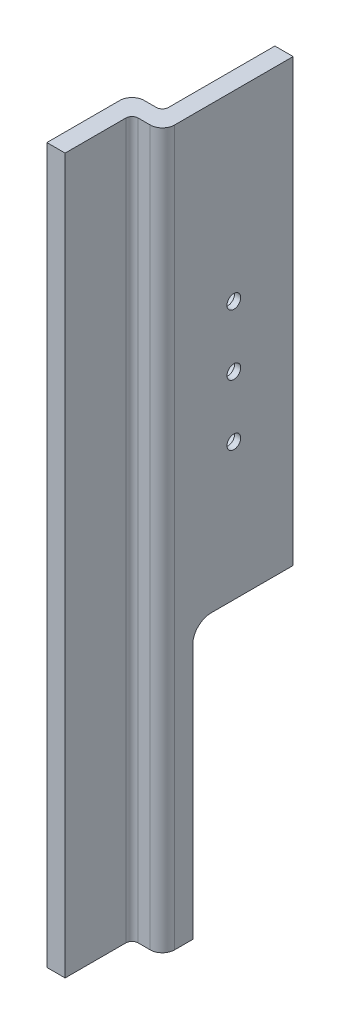
SolidWorks part; units mm, degrees
ref_plane "Piano frontale" through (0, 0, 0) normal (0, 0, 1) x (1, 0, 0)
ref_plane "Piano superiore" through (0, 0, 0) normal (0, 1, 0) x (1, 0, 0)
ref_plane "Piano destro" through (0, 0, 0) normal (1, 0, 0) x (0, 0, -1)
ref_plane "Piano1" through (6, 0, 0) normal (1, 0, 0) x (0, 0, -1)
sketch "Schizzo1" plane through (6, 0, 0) normal (1, 0, 0) x (0, 0, -1)
  line L0 (-28, 0) -> (37, 0)
  line L1 (37, 0) -> (37, 235)
  line L2 (37, 235) -> (-28, 235)
  line L3 (-28, 235) -> (-28, 0)
  dimension "D1" = 65
  dimension "D2" = 235
extrude "Estrusione-Estrusione1" add sketch "Schizzo1" against normal blind 16
sketch "Schizzo2" plane through (0, 0, 0) normal (0, -1, 0) x (1, 0, 0)
  line L0 (-10, -37) -> (0, -37)
  line L1 (0, -37) -> (0, 0)
  line L2 (0, 0) -> (-10, 0)
  line L3 (-10, 0) -> (-10, -37)
  line L4 (6, 28) -> (6, -37) construction
  dimension "D1" = 6
  dimension "D2" = 16
  dimension "D3" = 28
  dimension "D4" = 65
extrude "Taglio-Estrusione1" cut sketch "Schizzo2" against normal through all
sketch "Schizzo3" plane through (6, 0, 0) normal (1, 0, 0) x (0, 0, -1)
  line L0 (37, 0) -> (37, 90)
  line L1 (37, 90) -> (4, 90)
  line L2 (4, 90) -> (4, 0)
  line L3 (4, 0) -> (37, 0)
  line L4 (-28, 0) -> (37, 0) construction
  line L5 (-28, 235) -> (-28, 0) construction
  dimension "D1" = 32
  dimension "D2" = 65
  dimension "D3" = 90
extrude "Taglio-Estrusione2" cut sketch "Schizzo3" against normal through all
sketch "Schizzo4" plane through (0, 0, 0) normal (0, -1, 0) x (1, 0, 0)
  line L0 (6, 28) -> (-4, 28)
  line L1 (-4, 28) -> (-4, 6)
  line L2 (-4, 6) -> (6, 6)
  line L3 (6, 6) -> (6, 28)
  line L4 (6, 28) -> (6, -4) construction
  dimension "D1" = 10
  dimension "D2" = 22
extrude "Taglio-Estrusione3" cut sketch "Schizzo4" against normal through all
hole_wizard "Foro lamato per Vite M4 a testa esagonale-1" positions "Schizzo6" profile "Schizzo5" counterbore size "M4" standard "Ansi Metric"
sketch "Schizzo6" plane through (0, 0, 0) normal (-1, 0, 0) x (0, 0, 1)
  point P0 (-17.5, 175)
  point P1 (-17.5, 155)
  point P2 (-17.5, 135)
sketch "Schizzo5" plane through (0, 175, -17.5) normal (0, 1, 0) x (0, 0, 1)
  line L0 (0, 0) -> (0, 6)
  line L1 (0, 6) -> (2.25, 6)
  line L3 (2.25, 6) -> (2.25, 4)
  line L4 (2.25, 4) -> (4, 4)
  line L5 (4, 4) -> (4, 0)
  line L7 (4, 0) -> (0, 0)
  line L11 (0, -6.35) -> (0, 107.95) construction
  dimension "Thru Hole Dia." = 4.5
  dimension "Thru Hole Depth" = 6
  dimension "C'Bore Dia." = 8
  dimension "C'Bore Depth" = 4
fillet "Raccordo1" radius 2 2 edges at (0, 117.5, 0) (-4, 117.5, 6)
fillet "Raccordo2" radius 4 2 edges at (-10, 117.5, 0) (6, 117.5, 6)
fillet "Raccordo3" radius 6 1 edges at (3, 90, -4)
